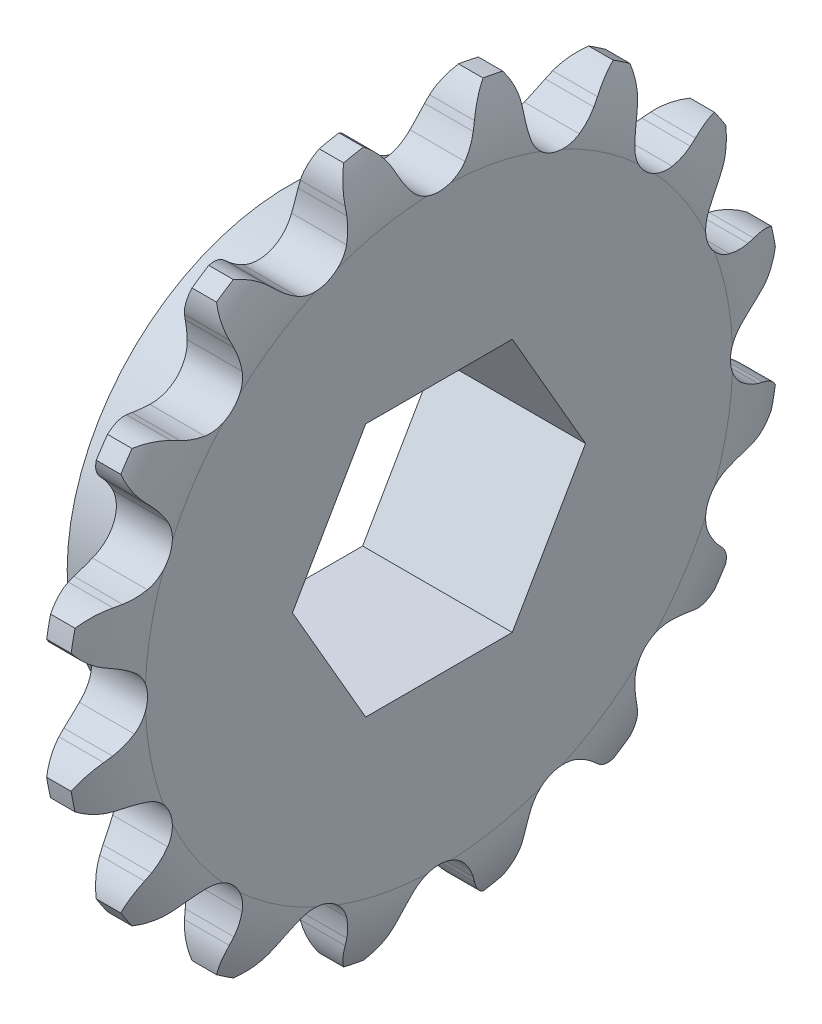
SolidWorks part; units mm, degrees
material "6061 Alloy"
ref_plane "Plane1" through (0, 0, 0) normal (0, 0, 1) x (1, 0, 0)
ref_plane "Plane2" through (0, 0, 0) normal (0, 1, 0) x (1, 0, 0)
ref_plane "Plane3" through (0, 0, 0) normal (1, 0, 0) x (0, 0, -1)
sketch "Clipboard" plane through (0, 0, 0) normal (0, 1, 0) x (1, 0, 0)
  line L0 (0, 0) -> (6.104, -1.7503)
  line L1 (-15, 0) -> (100, 0) construction
  line L2 (0, 0) -> (-0.5218, 0.5897)
  line L3 (0, 0) -> (-2.9658, 1.1335)
  line L4 (0, 0) -> (3.052, 0.8751)
  line L5 (0, 0) -> (-9.6384, -3.5949)
  line L6 (0, 0) -> (-2.3214, -1.5662)
  line L7 (-0.5218, 0.5897) -> (9.3158, 3.5974)
  line L8 (-76.2, 38.1) -> (-61.976, 38.1)
  line L9 (-73.2057, 38.5609) -> (-73.0533, 38.5634)
  line L10 (-73.0533, 76.1892) -> (-66.6525, 76.1892)
  circle A0 centre (0, 0) radius 1.651
  circle A1 centre (0, 0) radius 11.1125
  circle A2 centre (0, 0) radius 11.1125
  dimension "Dr" = 3.302
  dimension "MHD" = 22.225
  dimension "Hub_dia" = 22.225
  dimension "Num_teeth" = 16
  dimension "Pitch" = 6.35
  dimension "Width" = 3.175
  dimension "Chamfer_wid" = 0.7874
  dimension "Chamfer_dep" = 3.175
  dimension "Overall_len" = 10.287
  dimension "Show_teeth" = 16
  dimension "Thickness" = 2.8004
  dimension "OAL" = 10.2871
  dimension "T_dim" = 14.224
  dimension "Width_const" = 0.1524
  dimension "Width_factor" = 0.93
  dimension "Num_strands" = 1
  dimension "Transv_pitch" = 6.4008
sketch "BasProSke" plane through (0, 0, 0) normal (0, 1, 0) x (1, 0, 0)
  line L0 (-10, 0) -> (60, 0) construction
  line L1 (0, 0) -> (0, 14.6918)
  line L2 (0, 0) -> (2.8004, 0)
  line L3 (2.8004, 0) -> (2.8003, 14.6918)
  line L4 (2.013, 17.8668) -> (0.7874, 17.8668)
  arc A0 (0, 14.6918) -> (0.7874, 17.8668) centre (6.7949, 14.6918) cw
  arc A1 (2.8003, 14.6918) -> (2.013, 17.8668) centre (-3.9946, 14.6918) ccw
  dimension "D1" = 6.7949
  dimension "G1" = 0.7874
  dimension "G2" = 0.7874
  dimension "H2" = 3.175
  dimension "Diameter" = 35.7336
  dimension "H1" = 3.175
  dimension "Thickness" = 2.8004
revolve "Base-Revolve" add sketch "BasProSke" angle 360 about L0
sketch "GrvSke" plane through (0, 0, 0) normal (0, 1, 0) x (1, 0, 0)
  line L0 (2.8003, 14.6918) -> (2.8003, 12.4058)
  line L1 (2.8003, 12.4058) -> (6.4008, 12.4058)
  line L2 (6.4008, 12.4058) -> (6.4008, 14.6918)
  line L3 (2.0129, 17.8668) -> (7.1882, 17.8668)
  line L4 (4.6006, 0) -> (4.6006, 52.07) construction
  line L5 (-10, 0) -> (60, 0) construction
  line L6 (0, 0) -> (35.56, 0) construction
  arc A0 (6.4008, 14.6918) -> (7.1882, 17.8668) centre (13.1957, 14.6918) cw
  arc A1 (2.8003, 14.6918) -> (2.0129, 17.8668) centre (-3.9946, 14.6918) ccw
  dimension "Diameter" = 35.7336
  dimension "H1" = 3.175
  dimension "Grv_diam" = 24.8116
  dimension "Grv_width" = 3.6004
  dimension "Offset" = 4.6006
  dimension "G1" = 0.7874
revolve "Groove" [suppressed] cut sketch "GrvSke" angle 360 about L6
pattern_linear "Grooves" [suppressed]
sketch "TooCutSke" plane through (0, 0, 0) normal (1, 0, 0) x (0, 0, -1)
  line L0 (1.896, 16.1459) -> (2.0514, 16.491)
  line L1 (0, 0) -> (0, 107) construction
  line L2 (0, 16.2745) -> (-10, 16.2745) construction
  line L3 (-1.896, 16.1459) -> (-2.0514, 16.491)
  arc A0 (1.3237, 15.2121) -> (1.896, 16.1459) centre (-2.0601, 17.928) ccw
  arc A1 (1.3237, 15.2121) -> (-1.3237, 15.2121) centre (0, 16.2745) cw
  arc A2 (2.0514, 16.491) -> (4.534, 18.0955) centre (4.534, 15.3726) cw
  arc A3 (-1.3237, 15.2121) -> (-1.896, 16.1459) centre (2.0601, 17.928) cw
  arc A4 (-2.0514, 16.491) -> (-4.534, 18.0955) centre (-4.534, 15.3726) ccw
  arc A5 (4.534, 18.0955) -> (-4.534, 18.0955) centre (0, 0) ccw
  dimension "R" = 1.6974
  dimension "E" = 4.339
  dimension "F" = 2.7228
  dimension "Pitch_radius" = 16.2745
  dimension "W" = 4.534
  dimension "V" = 0.9019
  dimension "A" = 38.75
  dimension "B" = 14.5
extrude "ToothCut" cut sketch "TooCutSke" along normal through all
pattern_circular "TeethCuts" count 16 every 22.5 about axis through (-10, 0, 0) along (1, 0, 0) of "ToothCut"
sketch "HubNeaOneSke" plane through (0, 0, 0) normal (-1, 0, 0) x (0, 0, 1)
  circle A0 centre (0, 0) radius 11.1125
  dimension "Diameter" = 22.225
extrude "HubNearOne" add sketch "HubNeaOneSke" along normal blind 7.4867
sketch "HubNeaBotSke" plane through (0, 0, 0) normal (-1, 0, 0) x (0, 0, 1)
  circle A0 centre (0, 0) radius 11.1125
  dimension "Diameter" = 22.225
extrude "HubNearBoth" [suppressed] add sketch "HubNeaBotSke" along normal blind 3.7434
ref_plane "FarPln" through (2.8004, 0, 0) normal (1, 0, 0) x (0, 0, -1)
sketch "HubFarSke" plane through (2.8004, 0, 0) normal (1, 0, 0) x (0, 0, -1)
  circle A0 centre (0, 0) radius 11.1125
  dimension "Diameter" = 22.225
extrude "HubFar" [suppressed] add sketch "HubFarSke" along normal blind 3.7434
sketch "BorSke" plane through (0, 0, 0) normal (1, 0, 0) x (0, 0, -1)
  circle A0 centre (0, 0) radius 6.35
  dimension "Diameter" = 12.7
extrude "Bore" cut sketch "BorSke" along normal mid plane 20.5741
sketch "KeySke" plane through (0, 0, 0) normal (1, 0, 0) x (0, 0, -1)
  line L0 (-1.5875, 0) -> (-1.5875, 7.874)
  line L1 (-1.5875, 7.874) -> (1.5875, 7.874)
  line L2 (1.5875, 7.874) -> (1.5875, 0)
  line L3 (0, 0) -> (0, 34) construction
  line L4 (-1.5875, 0) -> (1.5875, 0)
  dimension "Offset" = 7.874
  dimension "Width" = 3.175
extrude "Keyway" [suppressed] cut sketch "KeySke" along normal mid plane 20.5741
pattern_circular "Keyway2" [suppressed] count 2 every 90 about axis through (-10, 0, 0) along (1, 0, 0)
sketch "Sketch1" plane through (2.8003, 0, 0) normal (1, 0, 0) x (0, 0, -1)
  line L1 (7.3323, 0) -> (3.6662, 6.35)
  line L2 (3.6662, 6.35) -> (-3.6662, 6.35)
  line L3 (-3.6662, 6.35) -> (-7.3323, 0)
  line L4 (-7.3323, 0) -> (-3.6662, -6.35)
  line L5 (-3.6662, -6.35) -> (3.6662, -6.35)
  line L6 (3.6662, -6.35) -> (7.3323, 0)
  circle A0 centre (0, 0) radius 6.35 construction
  circle A1 centre (0, 0) radius 6.35 construction
extrude "Cut-Extrude1" cut sketch "Sketch1" against normal through all
sketch "Sketch2" plane through (-7.4867, 0, 0) normal (-1, 0, 0) x (0, 0, 1)
  circle A0 centre (0, 0) radius 11.1125
  circle A1 centre (0, 0) radius 11.1125 construction
extrude "Cut-Extrude2" cut sketch "Sketch2" against normal up to surface (2.8003 mm away)
equation "\"Num_teeth@Clipboard\" = int( \"Num_teeth@Clipboard\" )"
equation "\"Num_teeth@Clipboard\" = ((sgn( \"Num_teeth@Clipboard\" - 5.0)+1)*( \"Num_teeth@Clipboard\" - 5.0))/2 +5.0"
equation "\"Num_teeth@Clipboard\" = ((sgn( \"Num_teeth@Clipboard\" - 200.0)-1)*( \"Num_teeth@Clipboard\" - 200.0))/-2 +200.0"
equation "\"MHD@Clipboard\" = \"Pitch@Clipboard\" * (1.0 / tan(3.14159265 / \"Num_teeth@Clipboard\" ) - 1.0) - 0.03"
equation "\"Thickness@Clipboard\"  = \"Width@Clipboard\" * \"Width_factor@Clipboard\" - \"Width_const@Clipboard\" + (\"Num_strands@Clipboard\" - 1) * \"Transv_pitch@Clipboard\""
equation "\"OAL@Clipboard\" = \"Thickness@Clipboard\""
equation "\"MHD@Clipboard\" = ((sgn( \"MHD@Clipboard\" - \"Hub_dia@Clipboard\" )-1)*( \"MHD@Clipboard\" - \"Hub_dia@Clipboard\" ))/-2+ \"Hub_dia@Clipboard\""
equation "\"OAL@Clipboard\" = ((sgn( \"OAL@Clipboard\" - \"Overall_len@Clipboard\" )+1)*( \"OAL@Clipboard\" - \"Overall_len@Clipboard\" ))/2 + \"Overall_len@Clipboard\" + 0.000002"
equation "\"Num_teeth@TeethCuts\" = int( \"Show_teeth@Clipboard\" ) + 1"
equation "\"Num_teeth@TeethCuts\" = ((sgn( \"Num_teeth@TeethCuts\" - \"Num_teeth@Clipboard\" )-1)*( \"Num_teeth@TeethCuts\" - \"Num_teeth@Clipboard\" ))/-2+ \"Num_teeth@Clipboard\""
equation "\"Num_teeth@TeethCuts\" = ((sgn( \"Num_teeth@TeethCuts\" - 2.0)+1)*( \"Num_teeth@TeethCuts\" - 2.0))/2 +2.0"
equation "\"Angle@TeethCuts\" = 360.0 / \"Num_teeth@Clipboard\""
equation "\"Pitch_radius@TooCutSke\" = ( \"Pitch@Clipboard\" / 2.0) / sin(3.14159265 / \"Num_teeth@Clipboard\" )  'ma"
equation "\"R@TooCutSke\"  = \"Dr@Clipboard\" * 0.5025 + 0.0015"
equation "\"A@TooCutSke\" = 35.0 + (60.0 / \"Num_teeth@Clipboard\")"
equation "\"E@TooCutSke\"  = \"Dr@Clipboard\" * 1.3025 + 0.0015"
equation "\"B@TooCutSke\"  = 18.0 - (56.0 / \"Num_teeth@Clipboard\" )"
equation "\"W@TooCutSke\" = 1.4 * \"Dr@Clipboard\" * cos(3.14159265 / \"Num_teeth@Clipboard\" )"
equation "\"V@TooCutSke\" = 1.4 * \"Dr@Clipboard\" * sin(3.14159265 / \"Num_teeth@Clipboard\" )"
equation "\"Diameter@BasProSke\" = 2.0 * ( (0.3 * \"Pitch@Clipboard\" ) +  \"Pitch@Clipboard\" / 2.0 / tan(3.14159265 / \"Num_teeth@Clipboard\" ))"
equation "\"Thickness@BasProSke\"  = \"Thickness@Clipboard\""
equation "\"G1@BasProSke\" =  \"Chamfer_wid@Clipboard\""
equation "\"G2@BasProSke\" =  \"Chamfer_wid@Clipboard\""
equation "\"H1@BasProSke\" =  \"Chamfer_dep@Clipboard\""
equation "\"H2@BasProSke\" =  \"Chamfer_dep@Clipboard\""
equation "\"Diameter@GrvSke\" = \"Diameter@BasProSke\""
equation "\"G1@GrvSke\" = \"Chamfer_wid@Clipboard\""
equation "\"H1@GrvSke\" = \"Chamfer_dep@Clipboard\""
equation "\"Grv_diam@GrvSke\" =  \"Pitch@Clipboard\" * (1.0 / tan(3.14159265 / \"Num_teeth@Clipboard\" ) - 1.0) - 0.03"
equation "\"Grv_width@GrvSke\" =  \"Transv_pitch@Clipboard\" - ( \"Width@Clipboard\" * \"Width_factor@Clipboard\" - \"Width_const@Clipboard\" )"
equation "\"Offset@GrvSke\" = \"Grv_width@GrvSke\" / 2.0 + ( \"Width@Clipboard\" * \"Width_factor@Clipboard\" - \"Width_const@Clipboard\" )"
equation "\"Offset@Grooves\" = \"Transv_pitch@Clipboard\""
equation "\"Num_grvs@Grooves\" = \"Num_strands@Clipboard\""
equation "\"Num_grvs@Grooves\" = \"Num_grvs@Grooves\" - 1 * sgn( \"Num_grvs@Grooves\" -1)"
equation "\"Diameter@HubNeaOneSke\" = \"MHD@Clipboard\""
equation "\"Length@HubNearOne\" = \"OAL@Clipboard\" - \"Thickness@BasProSke\""
equation "\"Diameter@HubNeaBotSke\" = \"MHD@Clipboard\""
equation "\"Length@HubNearBoth\" = ( \"OAL@Clipboard\" - \"Thickness@BasProSke\" ) / 2.0"
equation "\"Thickness@FarPln\" = \"Thickness@BasProSke\""
equation "\"Diameter@HubFarSke\" = \"MHD@Clipboard\""
equation "\"Length@HubFar\" = ( \"OAL@Clipboard\" - \"Thickness@BasProSke\" ) / 2.0"
equation "\"D1@Bore\" = \"OAL@Clipboard\" * 2.0"
equation "\"D1@Keyway\" = \"OAL@Clipboard\" * 2.0"
equation "\"Offset@KeySke\" = \"T_dim@Clipboard\" - \"Diameter@BorSke\" / 2.0"
